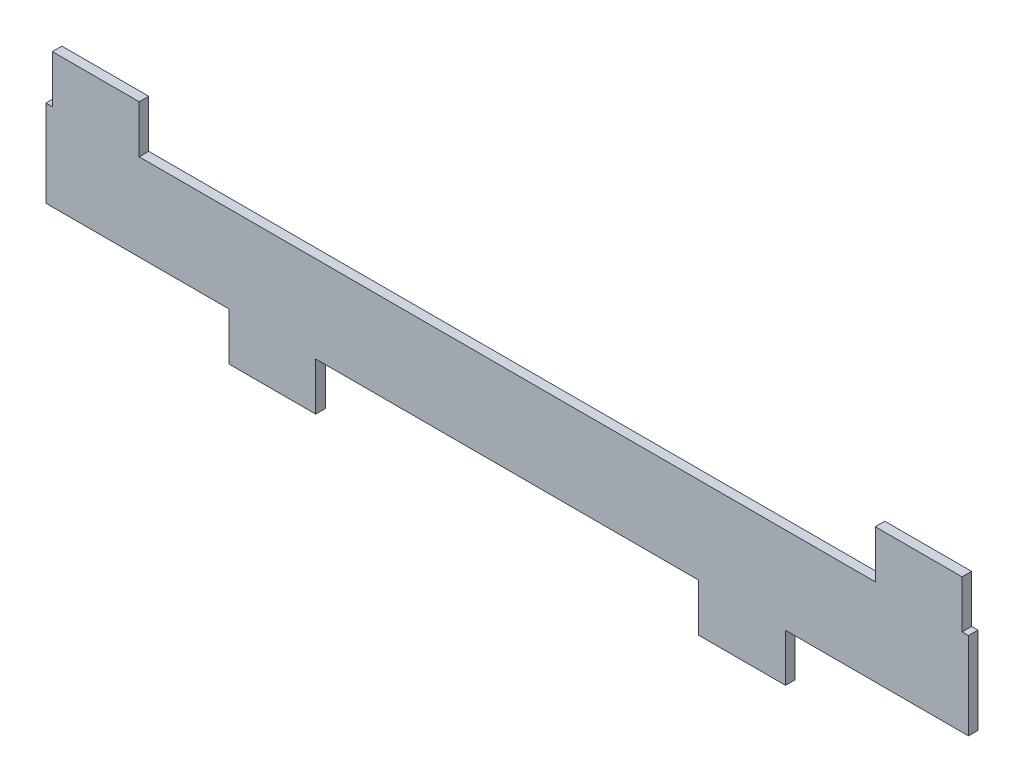
SolidWorks part; units mm, degrees
ref_plane "Front Plane" through (0, 0, 0) normal (0, 0, 1) x (1, 0, 0)
ref_plane "Top Plane" through (0, 0, 0) normal (0, 1, 0) x (1, 0, 0)
ref_plane "Right Plane" through (0, 0, 0) normal (1, 0, 0) x (0, 0, -1)
sketch "Model" plane through (0, 0, 0) normal (0, 0, 1) x (1, 0, 0)
  line L0 (325.3217, 71.8001) -> (325.3217, 99.1001)
  line L1 (35.3217, 99.1001) -> (35.3217, 71.8001)
  line L2 (323.3217, 99.1001) -> (323.3217, 114.1001)
  line L3 (37.3217, 114.1001) -> (37.3217, 99.1001)
  line L4 (37.3217, 99.1001) -> (35.3217, 99.1001)
  line L5 (35.3217, 71.8001) -> (92.8217, 71.8001)
  line L6 (323.3217, 99.1001) -> (325.3217, 99.1001)
  line L7 (325.3217, 71.8001) -> (267.8217, 71.8001)
  line L8 (64.6217, 114.1001) -> (64.6217, 99.1001)
  line L9 (296.0217, 99.1001) -> (296.0217, 114.1001)
  line L10 (64.6217, 99.1001) -> (296.0217, 99.1001)
  line L11 (64.6217, 114.1001) -> (37.3217, 114.1001)
  line L12 (296.0217, 114.1001) -> (323.3217, 114.1001)
  line L13 (92.8217, 56.8001) -> (120.1217, 56.8001)
  line L14 (120.1217, 56.8001) -> (120.1217, 71.8001)
  line L15 (92.8217, 71.8001) -> (92.8217, 56.8001)
  line L16 (267.8217, 56.8001) -> (240.5217, 56.8001)
  line L17 (240.5217, 56.8001) -> (240.5217, 71.8001)
  line L18 (267.8217, 71.8001) -> (267.8217, 56.8001)
  line L19 (120.1217, 71.8001) -> (240.5217, 71.8001)
  dimension "D1" = 290
  dimension "D2" = 286
  dimension "D3" = 2
  dimension "D4" = 27.3
  dimension "D5" = 27.3
  dimension "D6" = 27.3
  dimension "D7" = 15
  dimension "D8" = 15
  dimension "D9" = 15
  dimension "D10" = 27.3
  dimension "D11" = 27.3
  dimension "D12" = 175
extrude "Boss-Extrude1" add sketch "Model" along normal blind 3 contours L10 L9 L12 L2 L6 L0 L7 L18 L16 L17 L19 L14 L13 L15 L5 L1 L4 L3 L11 L8
